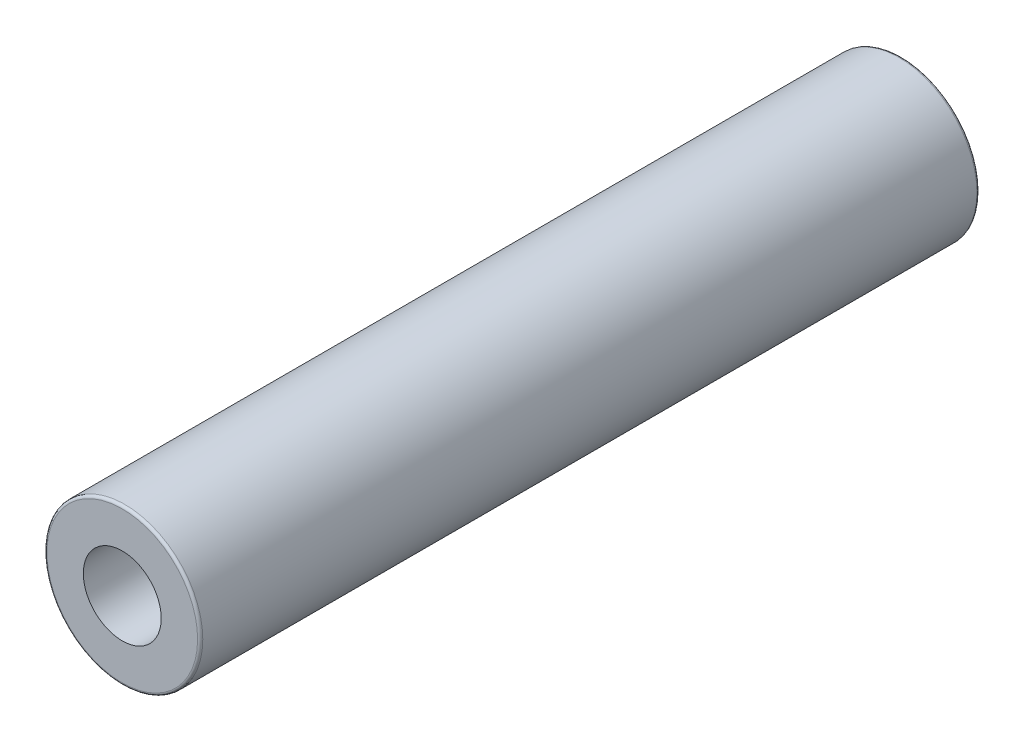
SolidWorks part; units mm, degrees
ref_plane "正面" through (0, 0, 0) normal (0, 0, 1) x (1, 0, 0)
ref_plane "平面" through (0, 0, 0) normal (0, 1, 0) x (1, 0, 0)
ref_plane "右側面" through (0, 0, 0) normal (1, 0, 0) x (0, 0, -1)
sketch "ｽｹｯﾁ1" plane through (0, 0, 0) normal (0, 0, 1) x (1, 0, 0)
  circle A0 centre (0, 0) radius 1.5
  circle A1 centre (0, 0) radius 3
  dimension "D1" = 6
  dimension "D2" = 3
extrude "ﾎﾞｽ - 押し出し1" add sketch "ｽｹｯﾁ1" along normal blind 30
fillet "ﾌｨﾚｯﾄ1" radius 0.1 2 edges at (3, 0, 0) (3, 0, 30)
